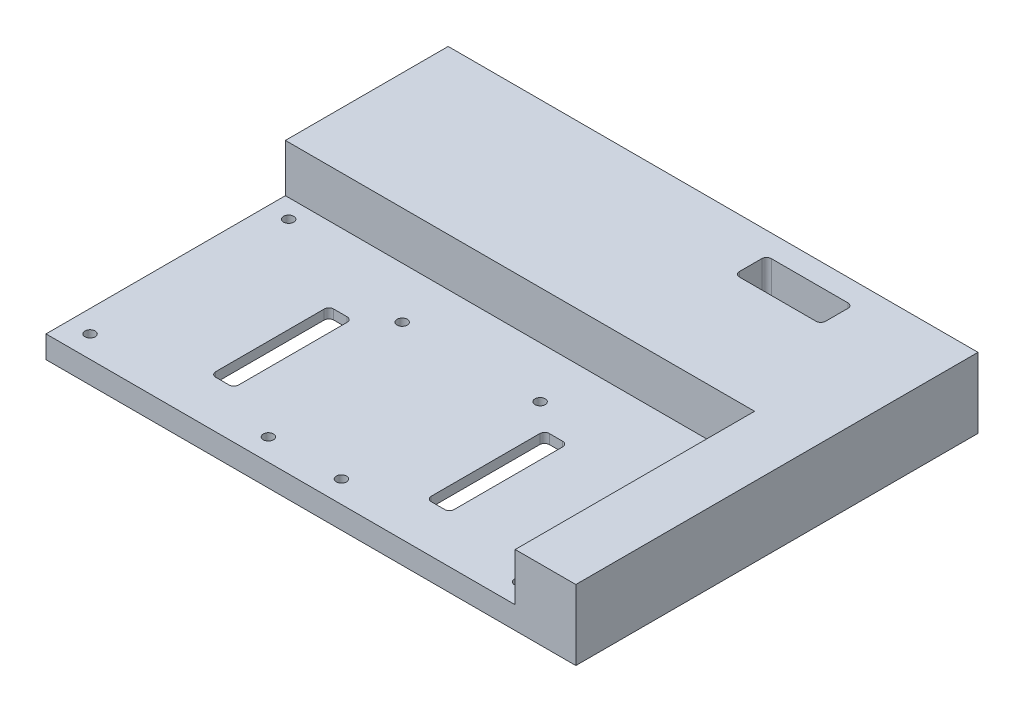
SolidWorks part; units mm, degrees
ref_plane "Front Plane" through (0, 0, 0) normal (0, 0, 1) x (1, 0, 0)
ref_plane "Top Plane" through (0, 0, 0) normal (0, 1, 0) x (1, 0, 0)
ref_plane "Right Plane" through (0, 0, 0) normal (1, 0, 0) x (0, 0, -1)
sketch "Sketch1" plane through (0, 0, 0) normal (0, 1, 0) x (1, 0, 0)
  line L1 (-83, 63) -> (83, 63)
  line L2 (-83, 63) -> (-83, -63)
  line L3 (-83, -63) -> (83, -63)
  line L4 (83, 63) -> (83, -63)
  dimension "D1" = 166
  dimension "D2" = 126
  dimension "D3" = 83
  dimension "D4" = 63
extrude "Boss-Extrude1" add sketch "Sketch1" along normal blind 7
sketch "Sketch2" plane through (0, 7, 0) normal (0, 1, 0) x (1, 0, 0)
  line L0 (-83, 63) -> (-83, 12)
  line L1 (-83, 63) -> (-83, -63) construction
  line L2 (-83, 12) -> (64, 12)
  line L3 (64, 12) -> (64, -63)
  line L4 (-83, -63) -> (83, -63) construction
  line L5 (64, -63) -> (83, -63)
  line L6 (83, -63) -> (83, 63) construction
  line L7 (83, -63) -> (83, 63)
  line L8 (83, 63) -> (-83, 63)
  dimension "D1" = 51
  dimension "D2" = 19
extrude "Boss-Extrude2" add sketch "Sketch2" along normal blind 15
sketch "Sketch3" plane through (0, 7, 0) normal (0, 1, 0) x (1, 0, 0)
  line L0 (-83, 12) -> (64, 12) construction
  line L1 (-44.67, -11.18) -> (-40.47, -11.18)
  line L2 (-46.17, -12.68) -> (-46.17, -46.68)
  line L3 (-44.67, -48.18) -> (-40.47, -48.18)
  line L4 (-38.97, -12.68) -> (-38.97, -46.68)
  line L5 (22.89, -11.19) -> (27.09, -11.19)
  line L6 (21.39, -12.69) -> (21.39, -46.69)
  line L7 (22.89, -48.19) -> (27.09, -48.19)
  line L8 (28.59, -12.69) -> (28.59, -46.69)
  line L10 (64, 12) -> (64, -63) construction
  arc A0 (27.09, -48.19) -> (28.59, -46.69) centre (27.09, -46.69) ccw
  arc A1 (28.59, -12.69) -> (27.09, -11.19) centre (27.09, -12.69) ccw
  arc A2 (22.89, -11.19) -> (21.39, -12.69) centre (22.89, -12.69) ccw
  arc A3 (22.89, -48.19) -> (21.39, -46.69) centre (22.89, -46.69) cw
  arc A4 (-44.67, -48.18) -> (-46.17, -46.68) centre (-44.67, -46.68) cw
  arc A5 (-40.47, -48.18) -> (-38.97, -46.68) centre (-40.47, -46.68) ccw
  arc A6 (-38.97, -12.68) -> (-40.47, -11.18) centre (-40.47, -12.68) ccw
  arc A7 (-46.17, -12.68) -> (-44.67, -11.18) centre (-44.67, -12.68) cw
  point P18 (-46.17, -48.18)
  point P25 (-46.17, -11.18)
  dimension "D3" = 1.5
  dimension "D1" = 37
  dimension "D2" = 7.2
  dimension "D4" = 67.56
  dimension "D5" = 23.18
  dimension "D6" = 23.19
  dimension "D7" = 102.97
extrude "Cut-Extrude1" cut sketch "Sketch3" against normal up to next
sketch "Sketch4" plane through (0, 7, 0) normal (0, 1, 0) x (1, 0, 0)
  line L0 (-83, 12) -> (-83, -63) construction
  line L1 (-83, -63) -> (64, -63) construction
  circle A0 centre (-76.1, -56.1) radius 1.6
  circle A1 centre (-20.22, -56.1) radius 1.6
  circle A2 centre (2.64, -56.1) radius 1.6
  circle A3 centre (58.49, -56.1) radius 1.6
  circle A4 centre (-76.1, 6.13) radius 1.6
  circle A5 centre (-30.38, -4.03) radius 1.6
  circle A6 centre (58.52, 6.16) radius 1.6
  circle A7 centre (12.8, -4) radius 1.6
  dimension "D1" = 3.2
  dimension "D2" = 3.2
  dimension "D3" = 3.2
  dimension "D4" = 3.2
  dimension "D5" = 3.2
  dimension "D6" = 3.2
  dimension "D7" = 3.2
  dimension "D8" = 3.2
  dimension "D9" = 22.86
  dimension "D10" = 55.88
  dimension "D11" = 55.85
  dimension "D12" = 45.72
  dimension "D13" = 10.16
  dimension "D14" = 62.23
  dimension "D15" = 62.26
  dimension "D16" = 10.16
  dimension "D17" = 45.72
  dimension "D18" = 43.18
  dimension "D19" = 6.9
  dimension "D20" = 6.9
extrude "Cut-Extrude2" cut sketch "Sketch4" against normal through all
sketch "Sketch5" plane through (0, 0, 0) normal (0, -1, 0) x (-1, 0, 0)
  line L0 (70.6, -58) -> (25.7054, -58)
  line L1 (-78, -56.5) -> (-78, 56.5)
  line L3 (78, -50.6) -> (78, 0.6446)
  line L4 (83, -63) -> (-83, -63) construction
  line L5 (83, 63) -> (83, -63) construction
  line L6 (-83, -63) -> (-83, 63) construction
  line L7 (14.7346, -58) -> (2.8454, -58)
  line L8 (-8.1254, -58) -> (-53.0046, -58)
  line L9 (-63.9754, -58) -> (-76.5, -58)
  line L11 (72.1, -56.1) -> (72.1, -56.5)
  line L12 (76.1, -52.1) -> (76.5, -52.1)
  line L13 (76.5, 58) -> (-76.5, 58)
  line L14 (-83, 63) -> (83, 63) construction
  line L15 (78, 11.6154) -> (78, 56.5)
  arc A0 (76.1, -52.1) -> (72.1, -56.1) centre (76.1, -56.1) ccw
  arc A1 (24.2094, -56.3909) -> (16.2306, -56.3909) centre (20.22, -56.1) ccw
  arc A2 (1.3494, -56.3909) -> (-6.6294, -56.3909) centre (-2.64, -56.1) ccw
  arc A3 (-54.5006, -56.3909) -> (-62.4794, -56.3909) centre (-58.49, -56.1) ccw
  circle A6 centre (30.38, -4.03) radius 4
  circle A7 centre (-12.8, -4) radius 4
  arc A8 (70.6, -58) -> (72.1, -56.5) centre (70.6, -56.5) ccw
  arc A9 (78, -50.6) -> (76.5, -52.1) centre (76.5, -50.6) cw
  arc A15 (-78, -56.5) -> (-76.5, -58) centre (-76.5, -56.5) ccw
  arc A16 (-63.9754, -58) -> (-62.4794, -56.3909) centre (-63.9754, -56.5) ccw
  arc A17 (-53.0046, -58) -> (-54.5006, -56.3909) centre (-53.0046, -56.5) cw
  arc A18 (-8.1254, -58) -> (-6.6294, -56.3909) centre (-8.1254, -56.5) ccw
  arc A19 (2.8454, -58) -> (1.3494, -56.3909) centre (2.8454, -56.5) cw
  arc A20 (14.7346, -58) -> (16.2306, -56.3909) centre (14.7346, -56.5) ccw
  arc A21 (24.2094, -56.3909) -> (25.7054, -58) centre (25.7054, -56.5) ccw
  arc A22 (76.3909, 10.1194) -> (76.3909, 2.1406) centre (76.1, 6.13) ccw
  circle A23 centre (-58.52, 6.16) radius 4
  arc A24 (78, 11.6154) -> (76.3909, 10.1194) centre (76.5, 11.6154) cw
  arc A25 (76.3909, 2.1406) -> (78, 0.6446) centre (76.5, 0.6446) cw
  arc A26 (-78, 56.5) -> (-76.5, 58) centre (-76.5, 56.5) cw
  arc A27 (76.5, 58) -> (78, 56.5) centre (76.5, 56.5) cw
  point P47 (78, 9.6499)
  point P59 (-62.0099, -58)
  point P64 (-6.1599, -58)
  point P69 (16.7001, -58)
  dimension "D1" = 8
  dimension "D2" = 8
  dimension "D3" = 5
  dimension "D4" = 8
  dimension "D5" = 8
  dimension "D6" = 8
  dimension "D7" = 8
  dimension "D8" = 8
  dimension "D13" = 1.5
  dimension "D14" = 1.5
  dimension "D15" = 1.5
  dimension "D12" = 8
  dimension "D16" = 1.5
  dimension "D17" = 1.5
  dimension "D9" = 5
  dimension "D10" = 5
  dimension "D11" = 5
extrude "Cut-Extrude3" cut sketch "Sketch5" against normal blind 4
sketch "Sketch6" plane through (0, 22, 0) normal (0, 1, 0) x (1, 0, 0)
  line L1 (25.2, 56.05) -> (49.2, 56.05)
  line L2 (23.7, 54.55) -> (23.7, 47.55)
  line L3 (25.2, 46.05) -> (49.2, 46.05)
  line L4 (50.7, 54.55) -> (50.7, 47.55)
  arc A0 (49.2, 56.05) -> (50.7, 54.55) centre (49.2, 54.55) cw
  arc A1 (50.7, 47.55) -> (49.2, 46.05) centre (49.2, 47.55) cw
  arc A2 (25.2, 46.05) -> (23.7, 47.55) centre (25.2, 47.55) cw
  arc A3 (25.2, 56.05) -> (23.7, 54.55) centre (25.2, 54.55) ccw
  point P7 (50.7, 56.05)
  point P10 (50.7, 46.05)
  point P13 (23.7, 46.05)
  dimension "D5" = 1.5
  dimension "D1" = 10
  dimension "D2" = 27
  dimension "D3" = 23.7
  dimension "D4" = 46.05
extrude "Cut-Extrude4" cut sketch "Sketch6" against normal through all
sketch "Sketch7" plane through (0, 4, 0) normal (0, -1, 0) x (1, 0, 0)
  line L1 (-27.5, -56) -> (-59.5, -56)
  line L2 (-26, -54.5) -> (-26, -27.5)
  line L3 (-27.5, -26) -> (-59.5, -26)
  line L4 (-61, -54.5) -> (-61, -27.5)
  arc A0 (-59.5, -56) -> (-61, -54.5) centre (-59.5, -54.5) cw
  arc A1 (-61, -27.5) -> (-59.5, -26) centre (-59.5, -27.5) cw
  arc A2 (-27.5, -26) -> (-26, -27.5) centre (-27.5, -27.5) cw
  arc A3 (-27.5, -56) -> (-26, -54.5) centre (-27.5, -54.5) ccw
  point P7 (-61, -56)
  point P10 (-61, -26)
  point P15 (-26, -56)
  dimension "D5" = 1.5
  dimension "D1" = 35
  dimension "D2" = 30
  dimension "D3" = 26
  dimension "D4" = 26
extrude "Cut-Extrude5" cut sketch "Sketch7" against normal blind 3
sketch "Sketch8" plane through (0, 4, 0) normal (0, -1, 0) x (1, 0, 0)
  line L1 (55.3, 45.9) -> (64.3, 45.9)
  line L2 (53.8, 44.4) -> (53.8, 29.4)
  line L3 (55.3, 27.9) -> (64.3, 27.9)
  line L4 (65.8, 44.4) -> (65.8, 29.4)
  arc A0 (53.8, 29.4) -> (55.3, 27.9) centre (55.3, 29.4) ccw
  arc A1 (64.3, 27.9) -> (65.8, 29.4) centre (64.3, 29.4) ccw
  arc A2 (65.8, 44.4) -> (64.3, 45.9) centre (64.3, 44.4) ccw
  arc A3 (55.3, 45.9) -> (53.8, 44.4) centre (55.3, 44.4) ccw
  point P10 (65.8, 27.9)
  point P13 (65.8, 45.9)
  point P16 (53.8, 45.9)
  dimension "D5" = 1.5
  dimension "D1" = 18
  dimension "D2" = 12
  dimension "D3" = 27.9
  dimension "D4" = 53.8
extrude "Cut-Extrude6" cut sketch "Sketch8" against normal blind 2
sketch "Sketch9" plane through (0, 4, 0) normal (0, -1, 0) x (-1, 0, 0)
  line L0 (-8.0828, -11.1128) -> (6.0593, 3.0293)
  line L1 (-8.0828, -13.2341) -> (6.0593, -27.3763)
  line L2 (8.1807, -27.3763) -> (22.3228, -13.2341)
  line L3 (22.3228, -11.1128) -> (8.1807, 3.0293)
  line L4 (22.3228, -11.1128) -> (7.12, 4.09) construction
  line L5 (-8.0828, -11.1128) -> (7.12, 4.09) construction
  arc A0 (-8.0828, -11.1128) -> (-8.0828, -13.2341) centre (-7.0221, -12.1735) ccw
  arc A1 (6.0593, 3.0293) -> (8.1807, 3.0293) centre (7.12, 1.9687) cw
  arc A2 (22.3228, -11.1128) -> (22.3228, -13.2341) centre (21.2621, -12.1735) cw
  arc A3 (6.0593, -27.3763) -> (8.1807, -27.3763) centre (7.12, -26.3156) ccw
  point P6 (-9.1435, -12.1735)
  point P13 (7.12, -28.4369)
  dimension "D2" = 1.5
  dimension "D1" = 23
  dimension "D3" = 4.09
  dimension "D4" = 7.12
extrude "Boss-Extrude3" add sketch "Sketch9" along normal blind 2
